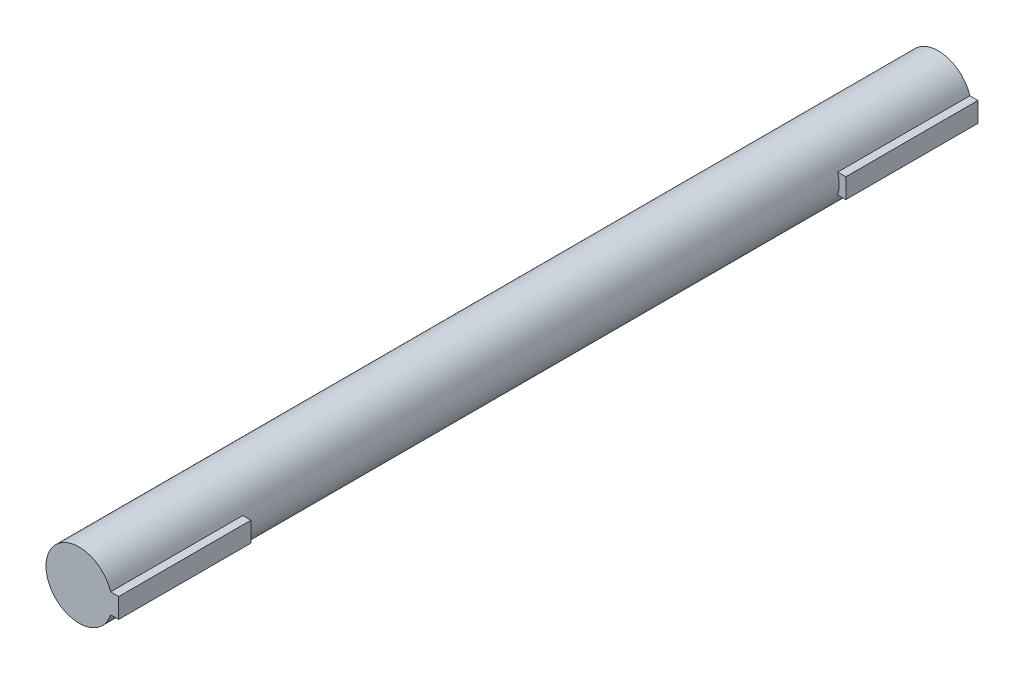
SolidWorks part; units mm, degrees
ref_plane "Front Plane" through (0, 0, 0) normal (0, 0, 1) x (1, 0, 0)
ref_plane "Top Plane" through (0, 0, 0) normal (0, 1, 0) x (1, 0, 0)
ref_plane "Right Plane" through (0, 0, 0) normal (1, 0, 0) x (0, 0, -1)
sketch "Sketch2" plane through (0, 0, 0) normal (0, 0, 1) x (1, 0, 0)
  circle A0 centre (0, 0) radius 10
extrude "Boss-Extrude5" add sketch "Sketch2" along normal blind 260
sketch "Sketch5" plane through (0, 0, 260) normal (0, 0, 1) x (1, 0, 0)
  line L0 (0, -3) -> (0, 3)
  line L1 (0, 3) -> (12, 3)
  line L2 (12, 3) -> (12, -3)
  line L3 (12, -3) -> (0, -3)
  point P4 (0, 0)
extrude "Boss-Extrude6" add sketch "Sketch5" against normal blind 40
sketch "Sketch6" plane through (0, 0, 0) normal (0, 0, -1) x (-1, 0, 0)
  line L0 (0, -3) -> (0, 3)
  line L1 (0, 3) -> (-12, 3)
  line L2 (-12, 3) -> (-12, -3)
  line L3 (-12, -3) -> (0, -3)
  point P4 (0, 0)
extrude "Boss-Extrude7" add sketch "Sketch6" against normal blind 40
